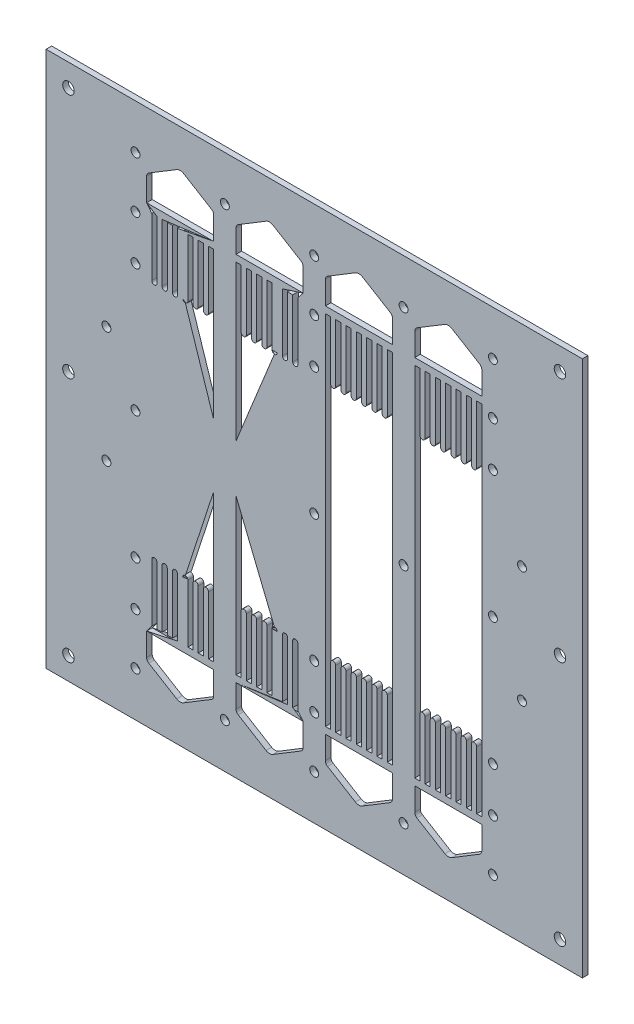
SolidWorks part; units mm, degrees
ref_plane "Front Plane" through (0, 0, 0) normal (0, 0, 1) x (1, 0, 0)
ref_plane "Top Plane" through (0, 0, 0) normal (0, 1, 0) x (1, 0, 0)
ref_plane "Right Plane" through (0, 0, 0) normal (1, 0, 0) x (0, 0, -1)
sketch "Sketch1" plane through (0, 0, 0) normal (0, 0, 1) x (1, 0, 0)
  line L0 (-152.4, 127) -> (-76.2, 127) construction
  line L1 (-152.4, 152.4) -> (152.4, 152.4)
  line L2 (-152.4, 152.4) -> (-152.4, -152.4)
  line L3 (-152.4, -152.4) -> (152.4, -152.4)
  line L4 (152.4, 152.4) -> (152.4, -152.4)
  line L5 (-76.2, 127) -> (-25.4, 127) construction
  line L6 (-25.4, 127) -> (25.4, 127) construction
  line L7 (25.4, 127) -> (76.2, 127) construction
  line L8 (76.2, 127) -> (152.4, 127) construction
  line L9 (-152.4, 0) -> (152.4, 0) construction
  line L10 (0, 152.4) -> (0, -152.4) construction
  line L11 (-118.11, 152.4) -> (-118.11, -152.4) construction
  line L12 (-152.4, -127) -> (152.4, -127) construction
  line L13 (127, 152.4) -> (127, -152.4) construction
  line L14 (-50.8, 152.4) -> (-50.8, -152.4) construction
  line L15 (50.8, 152.4) -> (50.8, -152.4) construction
  line L16 (-101.6, 152.4) -> (-101.6, -152.4) construction
  line L17 (-95.25, 66.04) -> (-57.15, 66.04) construction
  line L18 (-95.25, 66.04) -> (-95.25, -66.04)
  line L19 (-95.25, -66.04) -> (-57.15, -66.04) construction
  line L20 (-57.15, 66.04) -> (-57.15, -66.04)
  line L21 (-44.45, 66.04) -> (-6.35, 66.04) construction
  line L22 (-44.45, 66.04) -> (-44.45, -66.04)
  line L23 (-44.45, -66.04) -> (-6.35, -66.04) construction
  line L24 (-6.35, 66.04) -> (-6.35, -66.04)
  line L26 (6.35, 66.04) -> (6.35, -66.04)
  line L28 (44.45, 66.04) -> (44.45, -66.04)
  line L30 (57.15, 66.04) -> (57.15, -66.04)
  line L32 (95.25, 66.04) -> (95.25, -66.04)
  line L33 (101.6, 152.4) -> (101.6, -152.4) construction
  line L34 (-152.4, 120.65) -> (152.4, 120.65) construction
  line L35 (-101.6, 39.7057) -> (-95.25, 39.7057) construction
  line L36 (-57.15, 39.7057) -> (-50.8, 39.7057) construction
  line L37 (-76.2, 66.04) -> (-76.2, 0) construction
  line L38 (-76.2, 0) -> (-76.2, -66.04) construction
  line L39 (-152.4, 72.39) -> (152.4, 72.39) construction
  line L40 (-152.4, -72.39) -> (152.4, -72.39) construction
  line L41 (-76.2, 66.04) -> (-76.2, 72.39) construction
  line L42 (-95.25, -66.04) -> (-95.25, -72.39)
  line L43 (95.25, 39.7057) -> (101.6, 39.7057) construction
  line L44 (-95.25, 105.41) -> (-57.15, 105.41)
  line L45 (-57.15, 105.41) -> (-57.15, 118.4779)
  line L46 (-94.0266, 120.65) -> (-78.1749, 130.2582)
  line L47 (-95.25, 105.41) -> (-95.25, 118.4779)
  line L48 (-58.3734, 120.65) -> (-74.2251, 130.2582)
  line L49 (-107.3169, 130.81) -> (-83.1894, 130.81) construction
  line L50 (-6.35, 105.41) -> (-6.35, 118.4779)
  line L51 (-7.5734, 120.65) -> (-23.4251, 130.2582)
  line L52 (-43.2266, 120.65) -> (-27.3749, 130.2582)
  line L53 (-44.45, 105.41) -> (-44.45, 118.4779)
  line L54 (-6.35, 105.41) -> (-44.45, 105.41)
  line L55 (44.45, 105.41) -> (44.45, 118.4779)
  line L56 (43.2266, 120.65) -> (27.3749, 130.2582)
  line L57 (7.5734, 120.65) -> (23.4251, 130.2582)
  line L58 (6.35, 105.41) -> (6.35, 118.4779)
  line L59 (6.35, 105.41) -> (44.45, 105.41)
  line L60 (95.25, 105.41) -> (57.15, 105.41)
  line L61 (95.25, 105.41) -> (95.25, 118.4779)
  line L62 (94.0266, 120.65) -> (78.1749, 130.2582)
  line L63 (58.3734, 120.65) -> (74.2251, 130.2582)
  line L64 (57.15, 105.41) -> (57.15, 118.4779)
  line L65 (-95.25, -105.41) -> (-95.25, -118.4779)
  line L66 (-94.0266, -120.65) -> (-78.1749, -130.2582)
  line L67 (-58.3734, -120.65) -> (-74.2251, -130.2582)
  line L68 (-95.25, -105.41) -> (-57.15, -105.41)
  line L69 (-57.15, -105.41) -> (-57.15, -118.4779)
  line L70 (-44.45, -105.41) -> (-44.45, -118.4779)
  line L71 (-43.2266, -120.65) -> (-27.3749, -130.2582)
  line L72 (-6.35, -105.41) -> (-44.45, -105.41)
  line L73 (-7.5734, -120.65) -> (-23.4251, -130.2582)
  line L74 (-6.35, -105.41) -> (-6.35, -118.4779)
  line L75 (6.35, -105.41) -> (6.35, -118.4779)
  line L76 (7.5734, -120.65) -> (23.4251, -130.2582)
  line L77 (43.2266, -120.65) -> (27.3749, -130.2582)
  line L78 (6.35, -105.41) -> (44.45, -105.41)
  line L79 (44.45, -105.41) -> (44.45, -118.4779)
  line L80 (57.15, -105.41) -> (57.15, -118.4779)
  line L81 (58.3734, -120.65) -> (74.2251, -130.2582)
  line L82 (94.0266, -120.65) -> (78.1749, -130.2582)
  line L83 (95.25, -105.41) -> (57.15, -105.41)
  line L84 (95.25, -105.41) -> (95.25, -118.4779)
  line L85 (-152.4, 97.79) -> (152.4, 97.79) construction
  line L86 (-50.8, 39.7057) -> (-44.45, 39.7057) construction
  line L87 (-127, 152.4) -> (-127, -152.4) construction
  line L89 (-95.25, 101.6) -> (-92.3192, 101.6)
  line L90 (-95.25, 101.6) -> (-95.25, -101.6)
  line L96 (-90.8538, 101.6) -> (-90.8538, 68.58) construction
  line L97 (-89.3885, 101.6) -> (-89.3885, 68.58)
  line L98 (-92.3192, 101.6) -> (-92.3192, 68.58)
  line L99 (-83.5269, 101.6) -> (-83.5269, 68.58)
  line L100 (-86.4577, 101.6) -> (-86.4577, 68.58)
  line L101 (-89.3885, 101.6) -> (-86.4577, 101.6)
  line L102 (-77.6654, 101.6) -> (-77.6654, 68.58)
  line L103 (-80.5962, 101.6) -> (-80.5962, 68.58)
  line L104 (-83.5269, 101.6) -> (-80.5962, 101.6)
  line L105 (-71.8038, 101.6) -> (-71.8038, 68.58)
  line L106 (-74.7346, 101.6) -> (-74.7346, 68.58)
  line L107 (-77.6654, 101.6) -> (-74.7346, 101.6)
  line L108 (-65.9423, 101.6) -> (-65.9423, 68.58)
  line L109 (-68.8731, 101.6) -> (-68.8731, 68.58)
  line L110 (-71.8038, 101.6) -> (-68.8731, 101.6)
  line L111 (-60.0808, 101.6) -> (-60.0808, 68.58)
  line L112 (-63.0115, 101.6) -> (-63.0115, 68.58)
  line L113 (-65.9423, 101.6) -> (-63.0115, 101.6)
  line L114 (-57.15, -101.6) -> (-57.15, 101.6)
  line L115 (-60.0808, 101.6) -> (-57.15, 101.6)
  line L116 (-92.3192, 68.58) -> (-89.3885, 68.58) construction
  line L117 (-60.0808, -101.6) -> (-57.15, -101.6)
  line L118 (-60.0808, -101.6) -> (-60.0808, -68.58)
  line L119 (-63.0115, -101.6) -> (-63.0115, -68.58)
  line L120 (-65.9423, -101.6) -> (-65.9423, -68.58)
  line L121 (-65.9423, -101.6) -> (-63.0115, -101.6)
  line L122 (-68.8731, -101.6) -> (-68.8731, -68.58)
  line L123 (-71.8038, -101.6) -> (-68.8731, -101.6)
  line L124 (-71.8038, -101.6) -> (-71.8038, -68.58)
  line L125 (-74.7346, -101.6) -> (-74.7346, -68.58)
  line L126 (-77.6654, -101.6) -> (-74.7346, -101.6)
  line L127 (-77.6654, -101.6) -> (-77.6654, -68.58)
  line L128 (-80.5962, -101.6) -> (-80.5962, -68.58)
  line L129 (-83.5269, -101.6) -> (-80.5962, -101.6)
  line L130 (-83.5269, -101.6) -> (-83.5269, -68.58)
  line L131 (-86.4577, -101.6) -> (-86.4577, -68.58)
  line L132 (-89.3885, -101.6) -> (-86.4577, -101.6)
  line L133 (-89.3885, -101.6) -> (-89.3885, -68.58)
  line L134 (-92.3192, -101.6) -> (-92.3192, -68.58)
  line L135 (-95.25, -101.6) -> (-92.3192, -101.6)
  line L136 (-9.2808, 68.58) -> (-12.2115, 68.58) construction
  line L137 (6.35, 66.04) -> (44.45, 66.04) construction
  line L138 (-6.35, -66.04) -> (-6.35, -72.39)
  line L139 (-25.4, 66.04) -> (-25.4, 72.39) construction
  line L140 (-25.4, 0) -> (-25.4, -66.04) construction
  line L141 (-25.4, 66.04) -> (-25.4, 0) construction
  line L142 (-44.45, 66.04) -> (-44.45, -66.04)
  line L144 (-6.35, 66.04) -> (-6.35, -66.04)
  line L146 (-6.35, -101.6) -> (-9.2808, -101.6)
  line L147 (-9.2808, -101.6) -> (-9.2808, -68.58)
  line L148 (-12.2115, -101.6) -> (-12.2115, -68.58)
  line L149 (-12.2115, -101.6) -> (-15.1423, -101.6)
  line L150 (-15.1423, -101.6) -> (-15.1423, -68.58)
  line L151 (-18.0731, -101.6) -> (-18.0731, -68.58)
  line L152 (-18.0731, -101.6) -> (-21.0038, -101.6)
  line L153 (-21.0038, -101.6) -> (-21.0038, -68.58)
  line L154 (-23.9346, -101.6) -> (-23.9346, -68.58)
  line L155 (-23.9346, -101.6) -> (-26.8654, -101.6)
  line L156 (-26.8654, -101.6) -> (-26.8654, -68.58)
  line L157 (-29.7962, -101.6) -> (-29.7962, -68.58)
  line L158 (-29.7962, -101.6) -> (-32.7269, -101.6)
  line L159 (-32.7269, -101.6) -> (-32.7269, -68.58)
  line L160 (-35.6577, -101.6) -> (-38.5885, -101.6)
  line L161 (-35.6577, -101.6) -> (-35.6577, -68.58)
  line L162 (-38.5885, -101.6) -> (-38.5885, -68.58)
  line L163 (-41.5192, -101.6) -> (-41.5192, -68.58)
  line L164 (-41.5192, -101.6) -> (-44.45, -101.6)
  line L165 (-41.5192, 101.6) -> (-44.45, 101.6)
  line L166 (-44.45, -101.6) -> (-44.45, 101.6)
  line L167 (-35.6577, 101.6) -> (-38.5885, 101.6)
  line L168 (-38.5885, 101.6) -> (-38.5885, 68.58)
  line L169 (-41.5192, 101.6) -> (-41.5192, 68.58)
  line L170 (-29.7962, 101.6) -> (-32.7269, 101.6)
  line L171 (-32.7269, 101.6) -> (-32.7269, 68.58)
  line L172 (-35.6577, 101.6) -> (-35.6577, 68.58)
  line L173 (-23.9346, 101.6) -> (-26.8654, 101.6)
  line L174 (-26.8654, 101.6) -> (-26.8654, 68.58)
  line L175 (-29.7962, 101.6) -> (-29.7962, 68.58)
  line L176 (-18.0731, 101.6) -> (-21.0038, 101.6)
  line L177 (-21.0038, 101.6) -> (-21.0038, 68.58)
  line L178 (-23.9346, 101.6) -> (-23.9346, 68.58)
  line L179 (-12.2115, 101.6) -> (-15.1423, 101.6)
  line L180 (-15.1423, 101.6) -> (-15.1423, 68.58)
  line L181 (-18.0731, 101.6) -> (-18.0731, 68.58)
  line L182 (-9.2808, 101.6) -> (-9.2808, 68.58)
  line L183 (-12.2115, 101.6) -> (-12.2115, 68.58)
  line L184 (-6.35, 101.6) -> (-6.35, -101.6)
  line L185 (-6.35, 101.6) -> (-9.2808, 101.6)
  line L186 (6.35, 66.04) -> (6.35, -66.04)
  line L187 (6.35, -66.04) -> (44.45, -66.04) construction
  line L188 (44.45, 66.04) -> (44.45, -66.04)
  line L189 (25.4, 66.04) -> (25.4, 0) construction
  line L190 (25.4, 0) -> (25.4, -66.04) construction
  line L191 (25.4, 66.04) -> (25.4, 72.39) construction
  line L192 (6.35, -66.04) -> (6.35, -72.39)
  line L193 (9.2808, 68.58) -> (12.2115, 68.58) construction
  line L194 (6.35, 66.04) -> (6.35, -66.04)
  line L196 (44.45, 66.04) -> (44.45, -66.04)
  line L198 (6.35, 101.6) -> (9.2808, 101.6)
  line L199 (6.35, 101.6) -> (6.35, -101.6)
  line L200 (12.2115, 101.6) -> (12.2115, 68.58)
  line L201 (9.2808, 101.6) -> (9.2808, 68.58)
  line L202 (18.0731, 101.6) -> (18.0731, 68.58)
  line L203 (15.1423, 101.6) -> (15.1423, 68.58)
  line L204 (12.2115, 101.6) -> (15.1423, 101.6)
  line L205 (23.9346, 101.6) -> (23.9346, 68.58)
  line L206 (21.0038, 101.6) -> (21.0038, 68.58)
  line L207 (18.0731, 101.6) -> (21.0038, 101.6)
  line L208 (29.7962, 101.6) -> (29.7962, 68.58)
  line L209 (26.8654, 101.6) -> (26.8654, 68.58)
  line L210 (23.9346, 101.6) -> (26.8654, 101.6)
  line L211 (35.6577, 101.6) -> (35.6577, 68.58)
  line L212 (32.7269, 101.6) -> (32.7269, 68.58)
  line L213 (29.7962, 101.6) -> (32.7269, 101.6)
  line L214 (41.5192, 101.6) -> (41.5192, 68.58)
  line L215 (38.5885, 101.6) -> (38.5885, 68.58)
  line L216 (35.6577, 101.6) -> (38.5885, 101.6)
  line L217 (44.45, -101.6) -> (44.45, 101.6)
  line L218 (41.5192, 101.6) -> (44.45, 101.6)
  line L219 (41.5192, -101.6) -> (44.45, -101.6)
  line L220 (41.5192, -101.6) -> (41.5192, -68.58)
  line L221 (38.5885, -101.6) -> (38.5885, -68.58)
  line L222 (35.6577, -101.6) -> (35.6577, -68.58)
  line L223 (35.6577, -101.6) -> (38.5885, -101.6)
  line L224 (32.7269, -101.6) -> (32.7269, -68.58)
  line L225 (29.7962, -101.6) -> (32.7269, -101.6)
  line L226 (29.7962, -101.6) -> (29.7962, -68.58)
  line L227 (26.8654, -101.6) -> (26.8654, -68.58)
  line L228 (23.9346, -101.6) -> (26.8654, -101.6)
  line L229 (23.9346, -101.6) -> (23.9346, -68.58)
  line L230 (21.0038, -101.6) -> (21.0038, -68.58)
  line L231 (18.0731, -101.6) -> (21.0038, -101.6)
  line L232 (18.0731, -101.6) -> (18.0731, -68.58)
  line L233 (15.1423, -101.6) -> (15.1423, -68.58)
  line L234 (12.2115, -101.6) -> (15.1423, -101.6)
  line L235 (12.2115, -101.6) -> (12.2115, -68.58)
  line L236 (9.2808, -101.6) -> (9.2808, -68.58)
  line L237 (6.35, -101.6) -> (9.2808, -101.6)
  line L239 (57.15, 66.04) -> (57.15, -66.04)
  line L240 (57.15, -66.04) -> (95.25, -66.04) construction
  line L241 (95.25, 66.04) -> (95.25, -66.04)
  line L242 (92.3192, 68.58) -> (89.3885, 68.58) construction
  line L243 (95.25, -66.04) -> (95.25, -72.39)
  line L244 (76.2, 66.04) -> (76.2, 72.39) construction
  line L245 (76.2, 0) -> (76.2, -66.04) construction
  line L246 (76.2, 66.04) -> (76.2, 0) construction
  line L247 (57.15, 66.04) -> (57.15, -66.04)
  line L249 (95.25, 66.04) -> (95.25, -66.04)
  line L250 (95.25, 66.04) -> (57.15, 66.04) construction
  line L251 (57.15, 66.04) -> (57.15, -66.04)
  line L253 (95.25, 66.04) -> (95.25, -66.04)
  line L255 (95.25, -101.6) -> (92.3192, -101.6)
  line L256 (92.3192, -101.6) -> (92.3192, -68.58)
  line L257 (89.3885, -101.6) -> (89.3885, -68.58)
  line L258 (89.3885, -101.6) -> (86.4577, -101.6)
  line L259 (86.4577, -101.6) -> (86.4577, -68.58)
  line L260 (83.5269, -101.6) -> (83.5269, -68.58)
  line L261 (83.5269, -101.6) -> (80.5962, -101.6)
  line L262 (80.5962, -101.6) -> (80.5962, -68.58)
  line L263 (77.6654, -101.6) -> (77.6654, -68.58)
  line L264 (77.6654, -101.6) -> (74.7346, -101.6)
  line L265 (74.7346, -101.6) -> (74.7346, -68.58)
  line L266 (71.8038, -101.6) -> (71.8038, -68.58)
  line L267 (71.8038, -101.6) -> (68.8731, -101.6)
  line L268 (68.8731, -101.6) -> (68.8731, -68.58)
  line L269 (65.9423, -101.6) -> (63.0115, -101.6)
  line L270 (65.9423, -101.6) -> (65.9423, -68.58)
  line L271 (63.0115, -101.6) -> (63.0115, -68.58)
  line L272 (60.0808, -101.6) -> (60.0808, -68.58)
  line L273 (60.0808, -101.6) -> (57.15, -101.6)
  line L274 (60.0808, 101.6) -> (57.15, 101.6)
  line L275 (57.15, -101.6) -> (57.15, 101.6)
  line L276 (65.9423, 101.6) -> (63.0115, 101.6)
  line L277 (63.0115, 101.6) -> (63.0115, 68.58)
  line L278 (60.0808, 101.6) -> (60.0808, 68.58)
  line L279 (71.8038, 101.6) -> (68.8731, 101.6)
  line L280 (68.8731, 101.6) -> (68.8731, 68.58)
  line L281 (65.9423, 101.6) -> (65.9423, 68.58)
  line L282 (77.6654, 101.6) -> (74.7346, 101.6)
  line L283 (74.7346, 101.6) -> (74.7346, 68.58)
  line L284 (71.8038, 101.6) -> (71.8038, 68.58)
  line L285 (83.5269, 101.6) -> (80.5962, 101.6)
  line L286 (80.5962, 101.6) -> (80.5962, 68.58)
  line L287 (77.6654, 101.6) -> (77.6654, 68.58)
  line L288 (89.3885, 101.6) -> (86.4577, 101.6)
  line L289 (86.4577, 101.6) -> (86.4577, 68.58)
  line L290 (83.5269, 101.6) -> (83.5269, 68.58)
  line L291 (92.3192, 101.6) -> (92.3192, 68.58)
  line L292 (89.3885, 101.6) -> (89.3885, 68.58)
  line L293 (95.25, 101.6) -> (95.25, -101.6)
  line L294 (95.25, 101.6) -> (92.3192, 101.6)
  line L295 (-101.6, 39.7057) -> (-107.95, 39.7057) construction
  line L296 (-101.6, 78.74) -> (101.6, 78.74) construction
  line L297 (-107.95, 72.39) -> (-107.95, -72.39) construction
  line L298 (-101.6, -78.74) -> (101.6, -78.74) construction
  line L299 (107.95, 72.39) -> (107.95, -72.39) construction
  line L300 (-97.0611, 78.74) -> (-97.0611, 72.39) construction
  line L301 (-107.95, 22.225) -> (-120.65, 22.225) construction
  line L302 (-127, 15.875) -> (-127, -15.875) construction
  line L303 (-120.65, -22.225) -> (-107.95, -22.225) construction
  circle A0 centre (-76.2, 127) radius 3.3655 construction
  circle A1 centre (-25.4, 127) radius 3.3655 construction
  circle A2 centre (25.4, 127) radius 3.3655 construction
  circle A3 centre (76.2, 127) radius 3.3655 construction
  circle A4 centre (-101.6, 0) radius 2.54
  circle A5 centre (-50.8, 0) radius 2.54
  circle A6 centre (0, 0) radius 2.54
  circle A7 centre (101.6, 0) radius 2.54
  circle A8 centre (50.8, 0) radius 2.54
  circle A9 centre (-50.8, 127) radius 2.54
  circle A10 centre (0, 127) radius 2.54
  circle A11 centre (50.8, 127) radius 2.54
  circle A12 centre (-101.6, 72.39) radius 2.54
  circle A13 centre (0, 72.39) radius 2.54
  circle A14 centre (101.6, 72.39) radius 2.54
  circle A15 centre (-101.6, -72.39) radius 2.54
  circle A16 centre (0, -72.39) radius 2.54
  circle A17 centre (101.6, -72.39) radius 2.54
  arc A18 (-74.2251, 130.2582) -> (-78.1749, 130.2582) centre (-76.2, 127) ccw
  arc A19 (-57.15, 118.4779) -> (-58.3734, 120.65) centre (-59.69, 118.4779) ccw
  arc A20 (-95.25, 118.4779) -> (-94.0266, 120.65) centre (-92.71, 118.4779) cw
  arc A21 (-6.35, 118.4779) -> (-7.5734, 120.65) centre (-8.89, 118.4779) ccw
  arc A22 (-27.3749, 130.2582) -> (-23.4251, 130.2582) centre (-25.4, 127) cw
  arc A23 (-44.45, 118.4779) -> (-43.2266, 120.65) centre (-41.91, 118.4779) cw
  arc A24 (44.45, 118.4779) -> (43.2266, 120.65) centre (41.91, 118.4779) ccw
  arc A25 (27.3749, 130.2582) -> (23.4251, 130.2582) centre (25.4, 127) ccw
  arc A26 (6.35, 118.4779) -> (7.5734, 120.65) centre (8.89, 118.4779) cw
  arc A27 (95.25, 118.4779) -> (94.0266, 120.65) centre (92.71, 118.4779) ccw
  arc A28 (74.2251, 130.2582) -> (78.1749, 130.2582) centre (76.2, 127) cw
  arc A29 (57.15, 118.4779) -> (58.3734, 120.65) centre (59.69, 118.4779) cw
  circle A30 centre (-76.2, -127) radius 3.3655 construction
  circle A31 centre (-25.4, -127) radius 3.3655 construction
  circle A32 centre (25.4, -127) radius 3.3655 construction
  circle A33 centre (76.2, -127) radius 3.3655 construction
  arc A34 (-95.25, -118.4779) -> (-94.0266, -120.65) centre (-92.71, -118.4779) ccw
  arc A35 (-74.2251, -130.2582) -> (-78.1749, -130.2582) centre (-76.2, -127) cw
  arc A36 (-57.15, -118.4779) -> (-58.3734, -120.65) centre (-59.69, -118.4779) cw
  arc A37 (-44.45, -118.4779) -> (-43.2266, -120.65) centre (-41.91, -118.4779) ccw
  arc A38 (-27.3749, -130.2582) -> (-23.4251, -130.2582) centre (-25.4, -127) ccw
  arc A39 (-6.35, -118.4779) -> (-7.5734, -120.65) centre (-8.89, -118.4779) cw
  arc A40 (6.35, -118.4779) -> (7.5734, -120.65) centre (8.89, -118.4779) ccw
  arc A41 (27.3749, -130.2582) -> (23.4251, -130.2582) centre (25.4, -127) cw
  arc A42 (44.45, -118.4779) -> (43.2266, -120.65) centre (41.91, -118.4779) cw
  arc A43 (57.15, -118.4779) -> (58.3734, -120.65) centre (59.69, -118.4779) ccw
  arc A44 (74.2251, -130.2582) -> (78.1749, -130.2582) centre (76.2, -127) ccw
  arc A45 (95.25, -118.4779) -> (94.0266, -120.65) centre (92.71, -118.4779) cw
  circle A46 centre (50.8, -127) radius 2.54
  circle A47 centre (0, -127) radius 2.54
  circle A48 centre (-50.8, -127) radius 2.54
  circle A49 centre (-101.6, 97.79) radius 2.54
  circle A50 centre (0, 97.79) radius 2.54
  circle A51 centre (101.6, 97.79) radius 2.54
  circle A52 centre (101.6, 127) radius 2.54
  circle A53 centre (-101.6, 127) radius 2.54
  circle A54 centre (-118.11, 33.02) radius 2.54
  circle A56 centre (-101.6, -127) radius 2.54
  circle A57 centre (101.6, -127) radius 2.54
  circle A58 centre (101.6, -97.79) radius 2.54
  circle A59 centre (0, -97.79) radius 2.54
  circle A60 centre (-101.6, -97.79) radius 2.54
  circle A61 centre (-118.11, -33.02) radius 2.54
  circle A63 centre (-139.7, 139.7) radius 3.2639
  circle A64 centre (-139.7, 0) radius 3.2639
  circle A65 centre (-139.7, -139.7) radius 3.2639
  circle A66 centre (139.7, -139.7) radius 3.2639
  circle A67 centre (139.7, 0) radius 3.2639
  circle A68 centre (139.7, 139.7) radius 3.2639
  arc A70 (-92.3192, 68.58) -> (-89.3885, 68.58) centre (-90.8538, 68.58) ccw
  arc A71 (-86.4577, 68.58) -> (-83.5269, 68.58) centre (-84.9923, 68.58) ccw
  arc A72 (-80.5962, 68.58) -> (-77.6654, 68.58) centre (-79.1308, 68.58) ccw
  arc A73 (-74.7346, 68.58) -> (-71.8038, 68.58) centre (-73.2692, 68.58) ccw
  arc A74 (-68.8731, 68.58) -> (-65.9423, 68.58) centre (-67.4077, 68.58) ccw
  arc A75 (-63.0115, 68.58) -> (-60.0808, 68.58) centre (-61.5462, 68.58) ccw
  arc A76 (-63.0115, -68.58) -> (-60.0808, -68.58) centre (-61.5462, -68.58) cw
  arc A77 (-68.8731, -68.58) -> (-65.9423, -68.58) centre (-67.4077, -68.58) cw
  arc A78 (-74.7346, -68.58) -> (-71.8038, -68.58) centre (-73.2692, -68.58) cw
  arc A79 (-80.5962, -68.58) -> (-77.6654, -68.58) centre (-79.1308, -68.58) cw
  arc A80 (-86.4577, -68.58) -> (-83.5269, -68.58) centre (-84.9923, -68.58) cw
  arc A81 (-92.3192, -68.58) -> (-89.3885, -68.58) centre (-90.8538, -68.58) cw
  arc A82 (-9.2808, -68.58) -> (-12.2115, -68.58) centre (-10.7462, -68.58) ccw
  arc A83 (-15.1423, -68.58) -> (-18.0731, -68.58) centre (-16.6077, -68.58) ccw
  arc A84 (-21.0038, -68.58) -> (-23.9346, -68.58) centre (-22.4692, -68.58) ccw
  arc A85 (-26.8654, -68.58) -> (-29.7962, -68.58) centre (-28.3308, -68.58) ccw
  arc A86 (-32.7269, -68.58) -> (-35.6577, -68.58) centre (-34.1923, -68.58) ccw
  arc A87 (-38.5885, -68.58) -> (-41.5192, -68.58) centre (-40.0538, -68.58) ccw
  arc A88 (-38.5885, 68.58) -> (-41.5192, 68.58) centre (-40.0538, 68.58) cw
  arc A89 (-32.7269, 68.58) -> (-35.6577, 68.58) centre (-34.1923, 68.58) cw
  arc A90 (-26.8654, 68.58) -> (-29.7962, 68.58) centre (-28.3308, 68.58) cw
  arc A91 (-21.0038, 68.58) -> (-23.9346, 68.58) centre (-22.4692, 68.58) cw
  arc A92 (-15.1423, 68.58) -> (-18.0731, 68.58) centre (-16.6077, 68.58) cw
  arc A93 (-9.2808, 68.58) -> (-12.2115, 68.58) centre (-10.7462, 68.58) cw
  arc A94 (9.2808, 68.58) -> (12.2115, 68.58) centre (10.7462, 68.58) ccw
  arc A95 (15.1423, 68.58) -> (18.0731, 68.58) centre (16.6077, 68.58) ccw
  arc A96 (21.0038, 68.58) -> (23.9346, 68.58) centre (22.4692, 68.58) ccw
  arc A97 (26.8654, 68.58) -> (29.7962, 68.58) centre (28.3308, 68.58) ccw
  arc A98 (32.7269, 68.58) -> (35.6577, 68.58) centre (34.1923, 68.58) ccw
  arc A99 (38.5885, 68.58) -> (41.5192, 68.58) centre (40.0538, 68.58) ccw
  arc A100 (38.5885, -68.58) -> (41.5192, -68.58) centre (40.0538, -68.58) cw
  arc A101 (32.7269, -68.58) -> (35.6577, -68.58) centre (34.1923, -68.58) cw
  arc A102 (26.8654, -68.58) -> (29.7962, -68.58) centre (28.3308, -68.58) cw
  arc A103 (21.0038, -68.58) -> (23.9346, -68.58) centre (22.4692, -68.58) cw
  arc A104 (15.1423, -68.58) -> (18.0731, -68.58) centre (16.6077, -68.58) cw
  arc A105 (9.2808, -68.58) -> (12.2115, -68.58) centre (10.7462, -68.58) cw
  arc A106 (92.3192, -68.58) -> (89.3885, -68.58) centre (90.8538, -68.58) ccw
  arc A107 (86.4577, -68.58) -> (83.5269, -68.58) centre (84.9923, -68.58) ccw
  arc A108 (80.5962, -68.58) -> (77.6654, -68.58) centre (79.1308, -68.58) ccw
  arc A109 (74.7346, -68.58) -> (71.8038, -68.58) centre (73.2692, -68.58) ccw
  arc A110 (68.8731, -68.58) -> (65.9423, -68.58) centre (67.4077, -68.58) ccw
  arc A111 (63.0115, -68.58) -> (60.0808, -68.58) centre (61.5462, -68.58) ccw
  arc A112 (63.0115, 68.58) -> (60.0808, 68.58) centre (61.5462, 68.58) cw
  arc A113 (68.8731, 68.58) -> (65.9423, 68.58) centre (67.4077, 68.58) cw
  arc A114 (74.7346, 68.58) -> (71.8038, 68.58) centre (73.2692, 68.58) cw
  arc A115 (80.5962, 68.58) -> (77.6654, 68.58) centre (79.1308, 68.58) cw
  arc A116 (86.4577, 68.58) -> (83.5269, 68.58) centre (84.9923, 68.58) cw
  arc A117 (92.3192, 68.58) -> (89.3885, 68.58) centre (90.8538, 68.58) cw
  arc A118 (-101.6, 78.74) -> (-107.95, 72.39) centre (-101.6, 72.39) ccw construction
  arc A119 (-107.95, -72.39) -> (-101.6, -78.74) centre (-101.6, -72.39) ccw construction
  arc A120 (101.6, 78.74) -> (107.95, 72.39) centre (101.6, 72.39) cw construction
  arc A121 (101.6, -78.74) -> (107.95, -72.39) centre (101.6, -72.39) ccw construction
  arc A122 (-127, -15.875) -> (-120.65, -22.225) centre (-120.65, -15.875) ccw construction
  arc A123 (-120.65, 22.225) -> (-127, 15.875) centre (-120.65, 15.875) ccw construction
  circle A124 centre (118.11, -33.02) radius 2.54
  circle A125 centre (118.11, 33.02) radius 2.54
  point P10 (-76.2, 105.41)
  point P63 (50.8, 127)
  point P95 (-76.2, 66.04)
  point P97 (-25.4, 66.04)
  point P116 (-95.25, 0)
  point P118 (-44.45, 0)
  point P119 (6.35, 0)
  point P120 (57.15, 0)
  point P219 (-76.2, 33.02)
  point P259 (0, 78.74)
  point P260 (-107.95, 0)
  point P545 (-127, 0)
  point P548 (-127, -22.225)
  point P551 (-127, 22.225)
  dimension "D1" = 6.731
  dimension "D7" = 5.08
  dimension "D11" = 7.62
  dimension "D13" = 2.54
  dimension "D19" = 6.5278
  dimension "D25" = 6.35
  dimension "D26" = 6.35
  dimension "D27" = 6.35
  dimension "D29" = 6.35
  dimension "D2" = 25.4
  dimension "D3" = 50.8
  dimension "D4" = 25.4
  dimension "D5" = 25.4
  dimension "D6" = 25.4
  dimension "D8" = 38.1
  dimension "D9" = 31.75
  dimension "D10" = 132.08
  dimension "D12" = 19.05
  dimension "D14" = 25.4
  dimension "D15" = 304.8
  dimension "D16" = 304.8
  dimension "D17" = 8.89
  dimension "D18" = 12.7
  dimension "D20" = 12.7
  dimension "D21" = 12.7
  dimension "D23" = 33.02
  dimension "D24" = 15.24
  dimension "D28" = 44.45
  dimension "D22" = 6
extrude "Boss-Extrude1" add sketch "Sketch1" along normal blind 3.175
